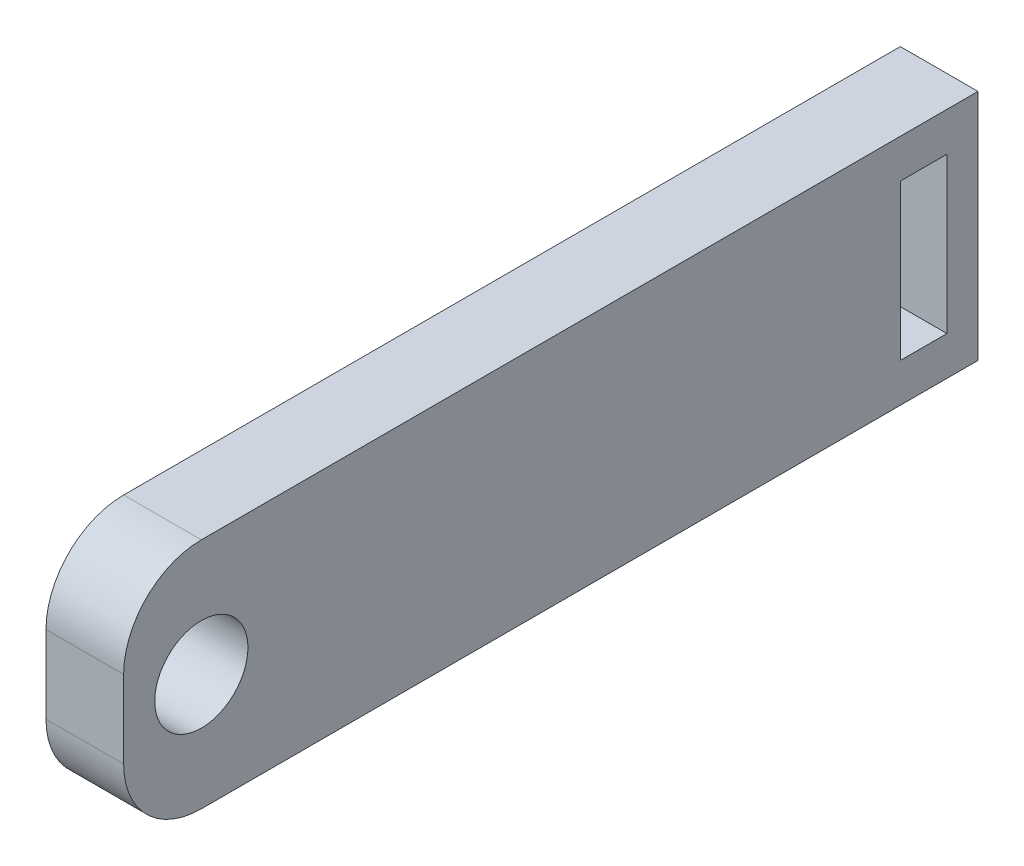
SolidWorks part; units mm, degrees
ref_plane "Front Plane" through (0, 0, 0) normal (0, 0, 1) x (1, 0, 0)
ref_plane "Top Plane" through (0, 0, 0) normal (0, 1, 0) x (1, 0, 0)
ref_plane "Right Plane" through (0, 0, 0) normal (1, 0, 0) x (0, 0, -1)
sketch "Sketch1" plane through (0, 0, 0) normal (0, 1, 0) x (1, 0, 0)
  line L1 (-61.8805, -26.2097) -> (-56.8805, -26.2097)
  line L2 (-61.8805, -26.2097) -> (-61.8805, 28.7903)
  line L3 (-61.8805, 28.7903) -> (-56.8805, 28.7903)
  line L4 (-56.8805, -26.2097) -> (-56.8805, 28.7903)
  line L6 (-56.8805, 28.7903) -> (-56.8805, 23.7903)
  dimension "D5" = 5
extrude "Boss-Extrude1" add sketch "Sketch1" along normal blind 15 contours L1 L4 L3 L2
sketch "Sketch2" plane through (-61.8805, 0, 0) normal (-1, 0, 0) x (0, 0, 1)
  line L2 (26.2097, 0) -> (-28.7903, 0) construction
  line L3 (-28.7903, 15) -> (-28.7903, 0) construction
  line L5 (-26.7903, 2.5) -> (-23.7903, 2.5)
  line L6 (-26.7903, 2.5) -> (-26.7903, 12.5)
  line L7 (-26.7903, 12.5) -> (-23.7903, 12.5)
  line L8 (-23.7903, 2.5) -> (-23.7903, 12.5)
  circle A0 centre (21.2097, 7.5) radius 3
  dimension "D3" = 6
  dimension "D1" = 7.5
  dimension "D2" = 50
  dimension "D4" = 2.5
  dimension "D5" = 10
  dimension "D6" = 2
  dimension "D7" = 3
extrude "Cut-Extrude1" cut sketch "Sketch2" against normal up to surface (5 mm away) up to face at (-56.8805, 7.5, -1.2903)
fillet "Fillet1" radius 5 2 edges at (-59.3805, 15, 26.2097) (-59.3805, 0, 26.2097)
